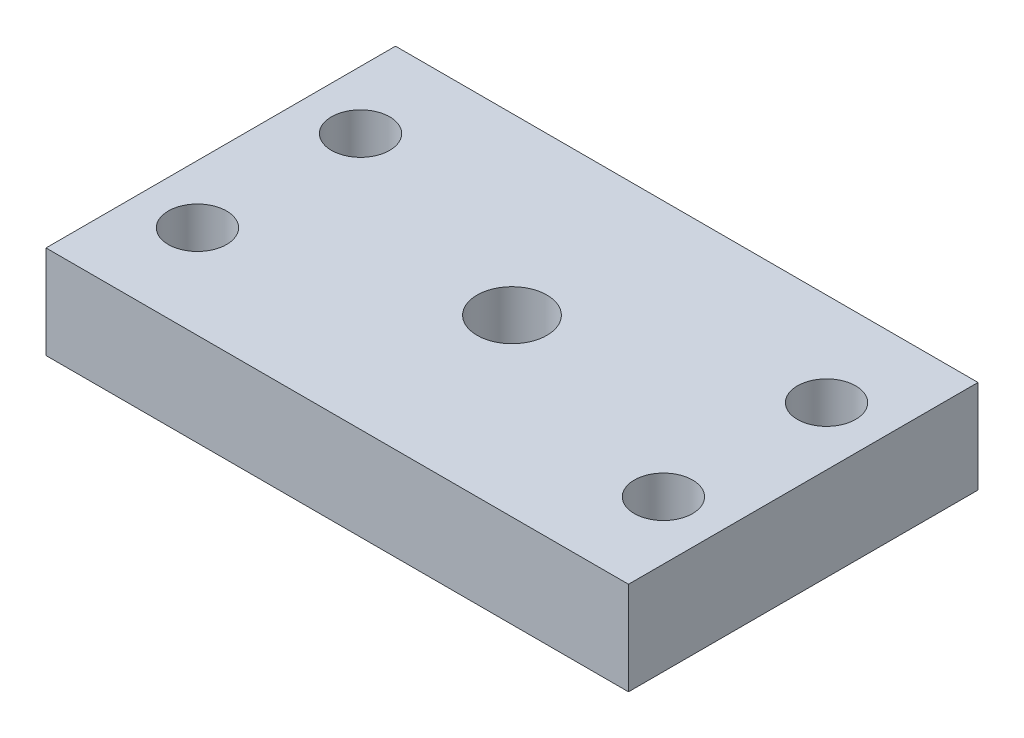
SolidWorks part; units mm, degrees
material "6061 合金"
ref_plane "前视基准面" through (0, 0, 0) normal (0, 0, 1) x (1, 0, 0)
ref_plane "上视基准面" through (0, 0, 0) normal (0, 1, 0) x (1, 0, 0)
ref_plane "右视基准面" through (0, 0, 0) normal (1, 0, 0) x (0, 0, -1)
sketch "草图1" plane through (0, 0, 0) normal (0, 1, 0) x (1, 0, 0)
  line L1 (0, 0) -> (25, 0)
  line L2 (0, 0) -> (0, -15)
  line L3 (0, -15) -> (25, -15)
  line L4 (25, 0) -> (25, -15)
  dimension "D1" = 25
  dimension "D2" = 15
extrude "凸台-拉伸1" add sketch "草图1" along normal blind 4
sketch "草图2" plane through (0, 4, 0) normal (0, 1, 0) x (1, 0, 0)
  line L0 (0, 0) -> (0, -15) construction
  line L1 (25, 0) -> (0, 0) construction
  line L2 (0, -15) -> (25, -15) construction
  line L3 (12.5, 0) -> (12.5, -15) construction
  circle A0 centre (2.5, -4) radius 1.25
  circle A1 centre (2.5, -11) radius 1.25
  circle A2 centre (22.5, -11) radius 1.25
  circle A3 centre (22.5, -4) radius 1.25
  circle A4 centre (12.5, -7.5) radius 1.5
  dimension "D1" = 2.5
  dimension "D2" = 2.5
  dimension "D3" = 4
  dimension "D4" = 4
  dimension "D5" = 3
  dimension "D6" = 2.5
extrude "切除-拉伸1" cut sketch "草图2" against normal blind 4
